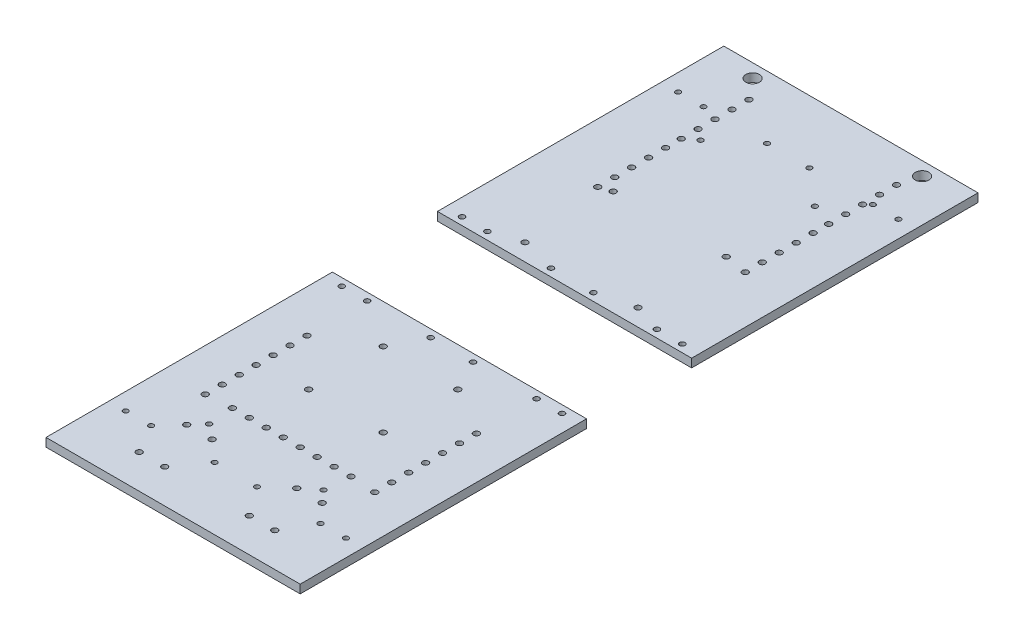
SolidWorks part; units mm, degrees
ref_plane "前视基准面" through (0, 0, 0) normal (0, 0, 1) x (1, 0, 0)
ref_plane "上视基准面" through (0, 0, 0) normal (0, 1, 0) x (1, 0, 0)
ref_plane "右视基准面" through (0, 0, 0) normal (1, 0, 0) x (0, 0, -1)
sketch "草图1" plane through (0, 0, 0) normal (0, 1, 0) x (1, 0, 0)
  line L0 (0, 200) -> (0, -200) construction
  line L1 (-75, 200) -> (75, 200)
  line L2 (-75, 200) -> (-75, -200)
  line L3 (-75, -200) -> (75, -200)
  line L4 (75, 200) -> (75, -200)
  line L5 (-75, 200) -> (75, -200) construction
  line L6 (-75, -200) -> (75, 200) construction
  line L7 (-75, 0) -> (75, 0) construction
  line L8 (-33.75, -145) -> (33.75, -145) construction
  line L9 (-33.75, 145) -> (33.75, 145) construction
  line L10 (-75, -163) -> (75, -163) construction
  circle A0 centre (-41.75, 0) radius 1.55
  circle A1 centre (41.75, 0) radius 1.55
  circle A2 centre (-33.75, -145) radius 1.55
  circle A3 centre (33.75, -145) radius 1.55
  circle A4 centre (-33.75, 145) radius 1.55
  circle A5 centre (33.75, 145) radius 1.55
  circle A6 centre (65, -163) radius 1.5
  circle A7 centre (50, -163) radius 1.5
  circle A8 centre (12.5, -163) radius 1.5
  circle A9 centre (-65, -163) radius 1.5
  circle A10 centre (-50, -163) radius 1.5
  circle A11 centre (-12.5, -163) radius 1.5
  circle A12 centre (65, 163) radius 1.5
  circle A13 centre (50, 163) radius 1.5
  circle A14 centre (12.5, 163) radius 1.5
  circle A15 centre (-12.5, 163) radius 1.5
  circle A16 centre (-50, 163) radius 1.5
  circle A17 centre (-65, 163) radius 1.5
  point P0 (0, 0)
  point P16 (0, -145)
  dimension "D3" = 3.1
  dimension "D4" = 83.5
  dimension "D8" = 3
  dimension "D9" = 10
  dimension "D10" = 15
  dimension "D11" = 25
  dimension "D1" = 150
  dimension "D2" = 400
  dimension "D5" = 67.5
  dimension "D6" = 145
  dimension "D7" = 18
extrude "凸台-拉伸1" add sketch "草图1" along normal blind 5
sketch "草图2" plane through (0, 5, 0) normal (0, 1, 0) x (1, 0, 0)
  line L0 (-75, 0) -> (75, 0) construction
  line L1 (-75, 200) -> (-75, -200) construction
  line L2 (75, -200) -> (75, 200) construction
  line L3 (0, 200) -> (0, -200) construction
  line L4 (75, 200) -> (-75, 200) construction
  line L5 (-75, -200) -> (75, -200) construction
  line L6 (-40.19, 135.395) -> (46.89, 135.395) construction
  line L7 (-40.19, 160) -> (46.89, 160) construction
  line L8 (-40.19, 160) -> (-40.19, 110.79) construction
  line L9 (-40.19, 110.79) -> (46.89, 110.79) construction
  line L10 (46.89, 160) -> (46.89, 110.79) construction
  line L11 (-40.19, 160) -> (46.89, 110.79) construction
  line L12 (-40.19, 110.79) -> (46.89, 160) construction
  line L13 (3.35, 160) -> (3.35, 110.79) construction
  line L14 (-31.075, 91.7365) -> (-33.35, 90.4231) construction
  line L15 (33.35, 90.4231) -> (35.625, 91.7365) construction
  line L16 (35.625, 91.7365) -> (35.625, 94.3635) construction
  line L17 (35.625, 94.3635) -> (33.35, 95.6769) construction
  line L18 (33.35, 95.6769) -> (31.075, 94.3635) construction
  line L19 (31.075, 94.3635) -> (31.075, 91.7365) construction
  line L20 (31.075, 91.7365) -> (33.35, 90.4231) construction
  line L21 (-31.075, 94.3635) -> (-31.075, 91.7365) construction
  line L22 (-33.35, 95.6769) -> (-31.075, 94.3635) construction
  line L23 (-35.625, 94.3635) -> (-33.35, 95.6769) construction
  line L24 (-35.625, 91.7365) -> (-35.625, 94.3635) construction
  line L25 (-33.35, 90.4231) -> (-35.625, 91.7365) construction
  line L26 (-33.35, 67.025) -> (33.35, 67.025) construction
  line L27 (-33.35, 93.05) -> (33.35, 93.05) construction
  line L28 (-33.35, 93.05) -> (-33.35, 41) construction
  line L29 (-33.35, 41) -> (33.35, 41) construction
  line L30 (33.35, 93.05) -> (33.35, 41) construction
  line L31 (-33.35, 93.05) -> (33.35, 41) construction
  line L32 (-33.35, 41) -> (33.35, 93.05) construction
  line L33 (-32.0365, 90.775) -> (-30.7231, 93.05) construction
  line L34 (-30.7231, 93.05) -> (-32.0365, 95.325) construction
  line L35 (-32.0365, 95.325) -> (-34.6635, 95.325) construction
  line L36 (-34.6635, 95.325) -> (-35.9769, 93.05) construction
  line L37 (-35.9769, 93.05) -> (-34.6635, 90.775) construction
  line L38 (-34.6635, 90.775) -> (-32.0365, 90.775) construction
  line L39 (-34.6635, 43.275) -> (-32.0365, 43.275) construction
  line L40 (-35.9769, 41) -> (-34.6635, 43.275) construction
  line L41 (-34.6635, 38.725) -> (-35.9769, 41) construction
  line L42 (-32.0365, 38.725) -> (-34.6635, 38.725) construction
  line L43 (-30.7231, 41) -> (-32.0365, 38.725) construction
  line L44 (-32.0365, 43.275) -> (-30.7231, 41) construction
  line L45 (-32.5, -152) -> (-32.5, -180) construction
  line L46 (-75, 31) -> (75, 31)
  line L47 (-75, 31) -> (-75, -31)
  line L48 (-75, -31) -> (75, -31)
  line L49 (75, 31) -> (75, -31)
  line L50 (-75, 31) -> (75, -31) construction
  line L51 (-75, -31) -> (75, 31) construction
  line L52 (-40, -152) -> (-25, -152) construction
  line L53 (-40, -152) -> (-40, -180) construction
  line L54 (-40, -180) -> (-25, -180) construction
  line L55 (-25, -152) -> (-25, -180) construction
  line L56 (-40, -152) -> (-25, -180) construction
  line L57 (-40, -180) -> (-25, -152) construction
  line L58 (-40, -166) -> (-25, -166) construction
  line L59 (-25, -76) -> (25, -76) construction
  line L60 (-25, -51) -> (25, -51) construction
  line L61 (-25, -51) -> (-25, -101) construction
  line L62 (-25, -101) -> (25, -101) construction
  line L63 (25, -51) -> (25, -101) construction
  line L64 (-25, -51) -> (25, -101) construction
  line L65 (-25, -101) -> (25, -51) construction
  line L66 (-75, 35.5) -> (75, 35.5) construction
  line L67 (-75, 40) -> (75, 40) construction
  line L68 (-75, 40) -> (-75, -40) construction
  line L69 (-75, -40) -> (75, -40) construction
  line L70 (75, 40) -> (75, -40) construction
  line L71 (-75, 40) -> (75, -40) construction
  line L72 (-75, -40) -> (75, 40) construction
  line L73 (-75, -35.5) -> (75, -35.5) construction
  circle A0 centre (-40.19, 160) radius 1.75
  circle A1 centre (46.89, 160) radius 1.75
  circle A2 centre (46.89, 110.79) radius 1.75
  circle A3 centre (-40.19, 110.79) radius 1.75
  circle A4 centre (-40.19, 170) radius 1.75
  circle A5 centre (-40.19, 120.79) radius 1.75
  circle A6 centre (46.89, 170) radius 1.75
  circle A7 centre (46.89, 120.79) radius 1.75
  circle A8 centre (-40.19, 180) radius 1.75
  circle A9 centre (-40.19, 130.79) radius 1.75
  circle A10 centre (46.89, 180) radius 1.75
  circle A11 centre (46.89, 130.79) radius 1.75
  circle A20 centre (33.35, 93.05) radius 2.275 construction
  circle A21 centre (-33.35, 93.05) radius 2.275 construction
  circle A22 centre (-33.35, 93.05) radius 1.75
  circle A23 centre (-33.35, 41) radius 1.75
  circle A24 centre (33.35, 41) radius 1.75
  circle A25 centre (33.35, 93.05) radius 1.75
  circle A26 centre (-40.19, 100.79) radius 1.75
  circle A27 centre (46.89, 100.79) radius 1.75
  circle A28 centre (-40.19, 150) radius 1.75
  circle A29 centre (46.89, 150) radius 1.75
  circle A30 centre (-40.19, 90.79) radius 1.75
  circle A31 centre (46.89, 90.79) radius 1.75
  circle A32 centre (-40.19, 140) radius 1.75
  circle A33 centre (46.89, 140) radius 1.75
  circle A34 centre (-40, -152) radius 1.75
  circle A35 centre (-25, -152) radius 1.75
  circle A36 centre (-25, -180) radius 1.75
  circle A37 centre (-40, -180) radius 1.75
  circle A38 centre (25, -152) radius 1.75
  circle A39 centre (25, -180) radius 1.75
  circle A40 centre (40, -180) radius 1.75
  circle A41 centre (40, -152) radius 1.75
  circle A42 centre (-22, -54) radius 1.75
  circle A43 centre (22, -54) radius 1.75
  circle A44 centre (22, -98) radius 1.75
  circle A45 centre (-22, -98) radius 1.75
  circle A46 centre (-50, -71) radius 1.75
  circle A47 centre (50, -71) radius 1.75
  circle A48 centre (50, -81) radius 1.75
  circle A49 centre (-50, -81) radius 1.75
  circle A50 centre (50, -91) radius 1.75
  circle A51 centre (-50, -91) radius 1.75
  circle A52 centre (50, -101) radius 1.75
  circle A53 centre (-50, -101) radius 1.75
  circle A54 centre (50, -111) radius 1.75
  circle A55 centre (-50, -111) radius 1.75
  circle A56 centre (50, -121) radius 1.75
  circle A57 centre (-50, -121) radius 1.75
  circle A58 centre (50, -131) radius 1.75
  circle A59 centre (-50, -131) radius 1.75
  circle A60 centre (-5, -130) radius 1.75
  circle A61 centre (5, -130) radius 1.75
  circle A62 centre (-15, -130) radius 1.75
  circle A63 centre (-25, -130) radius 1.75
  circle A64 centre (-35, -130) radius 1.75
  circle A65 centre (15, -130) radius 1.75
  circle A66 centre (25, -130) radius 1.75
  circle A67 centre (35, -130) radius 1.75
  circle A68 centre (-50, 192) radius 4
  circle A69 centre (50, 192) radius 4
  circle A70 centre (65, 35.5) radius 1.6
  circle A71 centre (50, 35.5) radius 1.6
  circle A72 centre (12.5, 35.5) radius 1.6
  circle A73 centre (-65, 35.5) radius 1.6
  circle A74 centre (-50, 35.5) radius 1.6
  circle A75 centre (-12.5, 35.5) radius 1.6
  circle A76 centre (65, -35.5) radius 1.6
  circle A77 centre (50, -35.5) radius 1.6
  circle A78 centre (12.5, -35.5) radius 1.6
  circle A79 centre (-12.5, -35.5) radius 1.6
  circle A80 centre (-50, -35.5) radius 1.6
  circle A81 centre (-65, -35.5) radius 1.6
  point P12 (3.35, 135.395)
  point P42 (0, 0)
  point P71 (32.2125, 91.0798)
  point P72 (0, 67.025)
  point P101 (-32.5, -166)
  point P122 (0, -76)
  point P185 (0, 0)
  dimension "D3" = 3.5
  dimension "D12" = 3.5
  dimension "D17" = 3.5
  dimension "D23" = 3
  dimension "D24" = 3
  dimension "D25" = 3.5
  dimension "D26" = 3.5
  dimension "D27" = 100
  dimension "D28" = 40
  dimension "D30" = 10
  dimension "D33" = 8
  dimension "D34" = 8
  dimension "D35" = 100
  dimension "D38" = 3.2
  dimension "D39" = 10
  dimension "D40" = 15
  dimension "D41" = 25
  dimension "D1" = 87.08
  dimension "D2" = 49.21
  dimension "D4" = 28.11
  dimension "D5" = 40
  dimension "D7" = 4.55
  dimension "D8" = 71.25
  dimension "D9" = 4.55
  dimension "D10" = 56.6
  dimension "D11" = 10
  dimension "D14" = 62
  dimension "D15" = 15
  dimension "D16" = 28
  dimension "D18" = 20
  dimension "D19" = 35
  dimension "D20" = 50
  dimension "D21" = 50
  dimension "D22" = 20
  dimension "D36" = 80
  dimension "D37" = 4.5
  dimension "D6" = 3
  dimension "D13" = 3
  dimension "D29" = 7
  dimension "D31" = 4
  dimension "D32" = 4
extrude "切除-拉伸1" cut sketch "草图2" against normal through all
